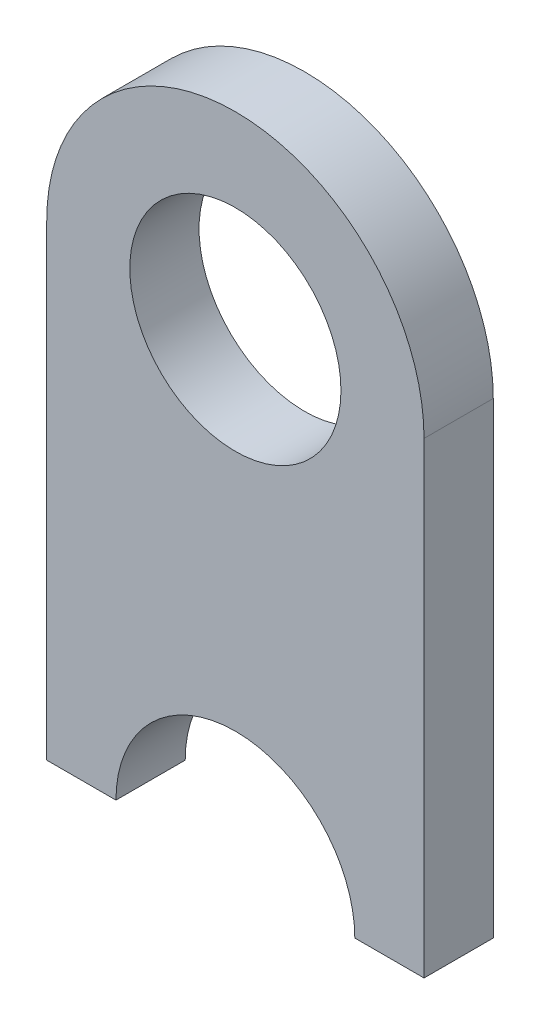
SolidWorks part; units mm, degrees
material "1023 탄소 강판(SS)"
ref_plane "정면" through (0, 0, 0) normal (0, 0, 1) x (1, 0, 0)
ref_plane "윗면" through (0, 0, 0) normal (0, 1, 0) x (1, 0, 0)
ref_plane "우측면" through (0, 0, 0) normal (1, 0, 0) x (0, 0, -1)
sketch "스케치1" plane through (0, 0, 0) normal (0, 0, 1) x (1, 0, 0)
  line L0 (0, 38.869) -> (0, -49.2447) construction
  line L1 (-10.9, 20.334) -> (-10.9, -6.666)
  line L2 (10.9, 20.334) -> (10.9, -6.666)
  line L3 (-10.9, -6.666) -> (-8.65, -6.666)
  line L4 (8.65, -6.666) -> (10.9, -6.666)
  line L5 (-8.65, -6.666) -> (-6.9, -6.666)
  line L6 (6.9, -6.666) -> (8.65, -6.666)
  circle A0 centre (0, 20.334) radius 6.1
  arc A1 (10.9, 20.334) -> (-10.9, 20.334) centre (0, 20.334) ccw
  arc A2 (6.9, -6.666) -> (-6.9, -6.666) centre (0, -6.666) ccw
  point P5 (10.9, 17.234)
  dimension "D1" = 12.2
  dimension "D2" = 21.8
  dimension "D3" = 27
  dimension "D4" = 2.25
  dimension "D6" = 27
  dimension "D7" = 13.8
  dimension "D5" = 2.25
extrude "보스-돌출1" add sketch "스케치1" along normal blind 4
